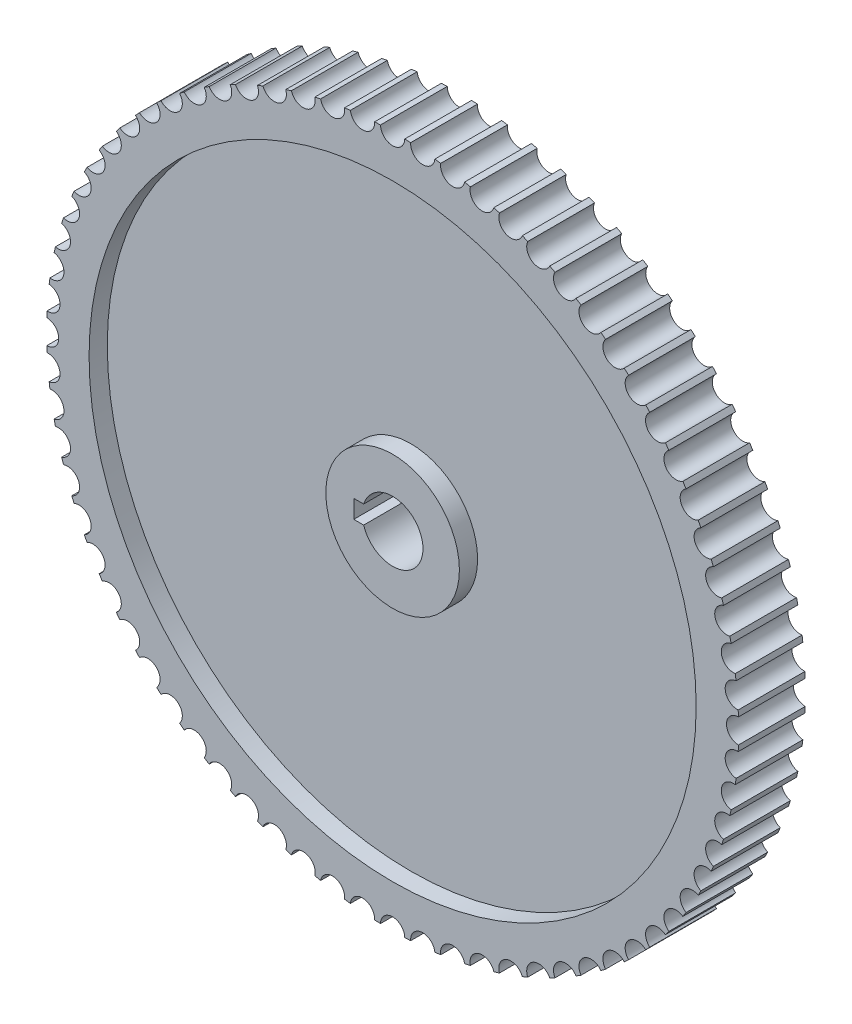
SolidWorks part; units mm, degrees
ref_plane "前视基准面" through (0, 0, 0) normal (0, 0, 1) x (1, 0, 0)
ref_plane "上视基准面" through (0, 0, 0) normal (0, 1, 0) x (1, 0, 0)
ref_plane "右视基准面" through (0, 0, 0) normal (1, 0, 0) x (0, 0, -1)
sketch "Sketch1" plane through (0, 0, 0) normal (0, 0, 1) x (1, 0, 0)
  circle A0 centre (0, 0) radius 57
  dimension "D1" = 114
extrude "Boss-Extrude1" add sketch "Sketch1" along normal blind 11
sketch "Sketch5" plane through (0, 0, 11) normal (0, 0, 1) x (1, 0, 0)
  circle A0 centre (0, 0) radius 5
extrude "Cut-Extrude4" cut sketch "Sketch5" against normal blind 10
sketch "KeySketch" plane through (-4.8256, -7.3318, 11) normal (0, 0, 1) x (1, 0, 0)
  line L0 (9.8256, 7.3318) -> (-1.5744, 7.3318) construction
  line L1 (4.8256, 2.3318) -> (4.8256, 12.3318) construction
  line L2 (0.0559, 5.8318) -> (-1.5744, 5.8318)
  line L3 (19.5602, 7.3318) -> (-9.4126, 7.3318) construction
  line L4 (-1.5744, 8.8318) -> (0.0559, 8.8318)
  line L5 (-1.5744, 8.8318) -> (-1.5744, 5.8318)
  arc A0 (0.0559, 5.8318) -> (0.0559, 8.8318) centre (4.8256, 7.3318) ccw
  circle A1 centre (4.8256, 7.3318) radius 5 construction
  point P10 (-1.5744, 7.3318)
  dimension "D1" = 0
  dimension "Diameter" = 10
  dimension "Width" = 3
  dimension "Depth" = 1.4
extrude "Keyway" cut sketch "KeySketch" against normal through all
other "bore with square keyway bs 4500p1<1>"
sketch "Sketch8" plane through (0, 0, 0) normal (0, 0, -1) x (-1, 0, 0)
  circle A0 centre (0, 0) radius 11
  circle A1 centre (0, 0) radius 50
  dimension "D1" = 100
extrude "Cut-Extrude6" cut sketch "Sketch8" against normal blind 3
sketch "Sketch9" plane through (0, 0, 11) normal (0, 0, 1) x (1, 0, 0)
  circle A0 centre (0, 0) radius 11
  circle A1 centre (0, 0) radius 50
  dimension "D1" = 100
extrude "Cut-Extrude7" cut sketch "Sketch9" against normal blind 3
sketch "Sketch10" plane through (0, 0, 11) normal (0, 0, 1) x (1, 0, 0)
  circle A0 centre (0, 57) radius 2
  circle A1 centre (0, 0) radius 57 construction
  circle A2 centre (4.9679, 56.7831) radius 2
  circle A3 centre (9.8979, 56.134) radius 2
  circle A4 centre (14.7527, 55.0578) radius 2
  circle A5 centre (19.4951, 53.5625) radius 2
  circle A6 centre (24.0892, 51.6595) radius 2
  circle A7 centre (28.5, 49.3634) radius 2
  circle A8 centre (32.6939, 46.6917) radius 2
  circle A9 centre (36.6389, 43.6645) radius 2
  circle A10 centre (40.3051, 40.3051) radius 2
  circle A11 centre (43.6645, 36.6389) radius 2
  circle A12 centre (46.6917, 32.6939) radius 2
  circle A13 centre (49.3634, 28.5) radius 2
  circle A14 centre (51.6595, 24.0892) radius 2
  circle A15 centre (53.5625, 19.4951) radius 2
  circle A16 centre (55.0578, 14.7527) radius 2
  circle A17 centre (56.134, 9.8979) radius 2
  circle A18 centre (56.7831, 4.9679) radius 2
  circle A19 centre (57, 0) radius 2
  circle A20 centre (56.7831, -4.9679) radius 2
  circle A21 centre (56.134, -9.8979) radius 2
  circle A22 centre (55.0578, -14.7527) radius 2
  circle A23 centre (53.5625, -19.4951) radius 2
  circle A24 centre (51.6595, -24.0892) radius 2
  circle A25 centre (49.3634, -28.5) radius 2
  circle A26 centre (46.6917, -32.6939) radius 2
  circle A27 centre (43.6645, -36.6389) radius 2
  circle A28 centre (40.3051, -40.3051) radius 2
  circle A29 centre (36.6389, -43.6645) radius 2
  circle A30 centre (32.6939, -46.6917) radius 2
  circle A31 centre (28.5, -49.3634) radius 2
  circle A32 centre (24.0892, -51.6595) radius 2
  circle A33 centre (19.4951, -53.5625) radius 2
  circle A34 centre (14.7527, -55.0578) radius 2
  circle A35 centre (9.8979, -56.134) radius 2
  circle A36 centre (4.9679, -56.7831) radius 2
  circle A37 centre (0, -57) radius 2
  circle A38 centre (-4.9679, -56.7831) radius 2
  circle A39 centre (-9.8979, -56.134) radius 2
  circle A40 centre (-14.7527, -55.0578) radius 2
  circle A41 centre (-19.4951, -53.5625) radius 2
  circle A42 centre (-24.0892, -51.6595) radius 2
  circle A43 centre (-28.5, -49.3634) radius 2
  circle A44 centre (-32.6939, -46.6917) radius 2
  circle A45 centre (-36.6389, -43.6645) radius 2
  circle A46 centre (-40.3051, -40.3051) radius 2
  circle A47 centre (-43.6645, -36.6389) radius 2
  circle A48 centre (-46.6917, -32.6939) radius 2
  circle A49 centre (-49.3634, -28.5) radius 2
  circle A50 centre (-51.6595, -24.0892) radius 2
  circle A51 centre (-53.5625, -19.4951) radius 2
  circle A52 centre (-55.0578, -14.7527) radius 2
  circle A53 centre (-56.134, -9.8979) radius 2
  circle A54 centre (-56.7831, -4.9679) radius 2
  circle A55 centre (-57, 0) radius 2
  circle A56 centre (-56.7831, 4.9679) radius 2
  circle A57 centre (-56.134, 9.8979) radius 2
  circle A58 centre (-55.0578, 14.7527) radius 2
  circle A59 centre (-53.5625, 19.4951) radius 2
  circle A60 centre (-51.6595, 24.0892) radius 2
  circle A61 centre (-49.3634, 28.5) radius 2
  circle A62 centre (-46.6917, 32.6939) radius 2
  circle A63 centre (-43.6645, 36.6389) radius 2
  circle A64 centre (-40.3051, 40.3051) radius 2
  circle A65 centre (-36.6389, 43.6645) radius 2
  circle A66 centre (-32.6939, 46.6917) radius 2
  circle A67 centre (-28.5, 49.3634) radius 2
  circle A68 centre (-24.0892, 51.6595) radius 2
  circle A69 centre (-19.4951, 53.5625) radius 2
  circle A70 centre (-14.7527, 55.0578) radius 2
  circle A71 centre (-9.8979, 56.134) radius 2
  circle A72 centre (-4.9679, 56.7831) radius 2
  dimension "D1" = 72
extrude "Cut-Extrude8" cut sketch "Sketch10" against normal blind 11
